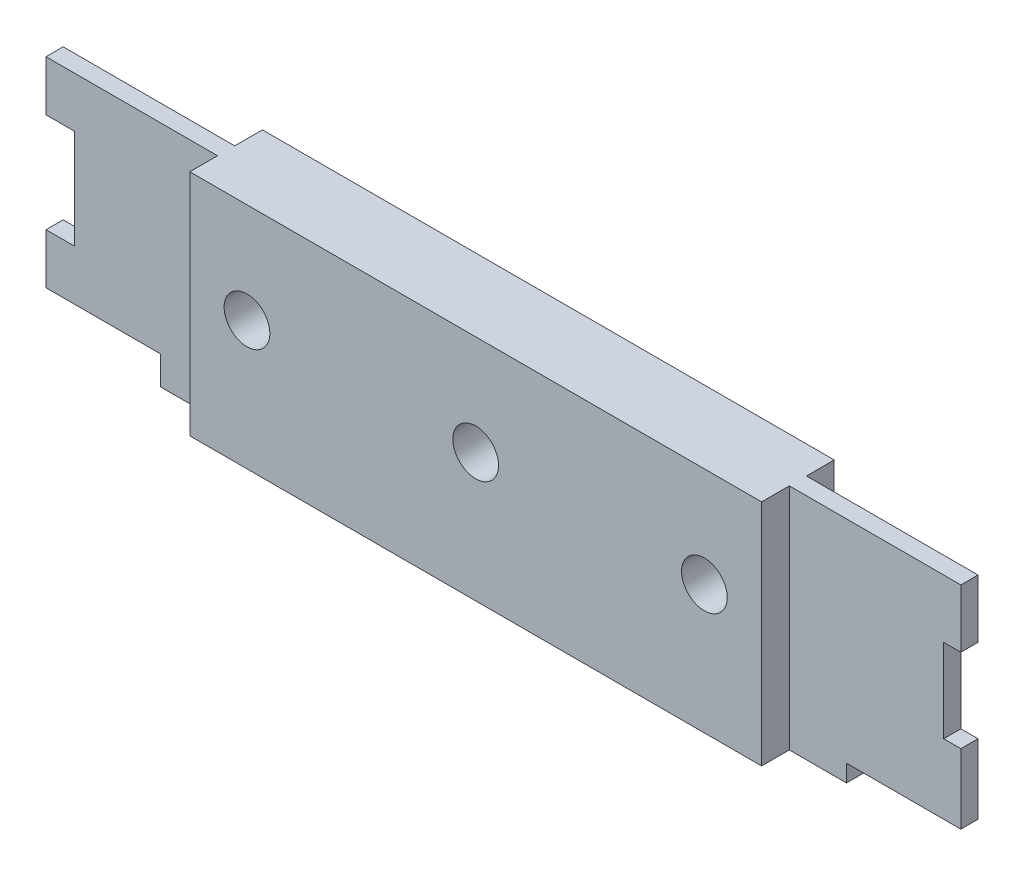
SolidWorks part; units mm, degrees
ref_plane "Alzado" through (0, 0, 0) normal (0, 0, 1) x (1, 0, 0)
ref_plane "Planta" through (0, 0, 0) normal (0, 1, 0) x (1, 0, 0)
ref_plane "Vista lateral" through (0, 0, 0) normal (1, 0, 0) x (0, 0, -1)
sketch "Croquis1" plane through (0, 0, 0) normal (0, 0, 1) x (1, 0, 0)
  line L0 (-40, 8.75) -> (40, 8.75)
  line L1 (40, 8.75) -> (40, 3.65)
  line L2 (40, 3.65) -> (38.5, 3.65)
  line L3 (38.5, 3.65) -> (38.5, -3.65)
  line L4 (38.5, -3.65) -> (40, -3.65)
  line L5 (40, -3.65) -> (40, -9.75)
  line L6 (40, -9.75) -> (30, -9.75)
  line L7 (30, -9.75) -> (30, -11.25)
  line L8 (30, -11.25) -> (-30, -11.25)
  line L9 (-30, -11.25) -> (-30, -8.75)
  line L10 (-30, -8.75) -> (-40, -8.75)
  line L11 (-40, -8.75) -> (-40, -4.35)
  line L12 (-40, -4.35) -> (-37.5, -4.35)
  line L13 (-37.5, -4.35) -> (-37.5, 4.35)
  line L14 (-37.5, 4.35) -> (-40, 4.35)
  line L15 (-40, 4.35) -> (-40, 8.75)
  line L16 (38.5, 0) -> (-37.5, 0) construction
  circle A0 centre (20, 0) radius 2
  circle A1 centre (0, 0) radius 2
  circle A2 centre (-20, 0) radius 2
  point P16 (-37.5, 0)
  point P18 (38.5, 0)
  point P19 (0, 8.75)
  dimension "D9" = 4
  dimension "D10" = 20
  dimension "D11" = 20
  dimension "D12" = 20
  dimension "D1" = 80
  dimension "D2" = 10
  dimension "D3" = 10
  dimension "D4" = 20
  dimension "D5" = 8.7
  dimension "D6" = 7.3
  dimension "D7" = 2.5
  dimension "D8" = 1.5
extrude "Saliente-Extruir1" add sketch "Croquis1" along normal mid plane 1.5
sketch "Croquis2" plane through (0, 0, 0) normal (0, 0, 1) x (1, 0, 0)
  line L0 (40, 8.75) -> (-40, 8.75) construction
  line L1 (-25, 8.75) -> (25, 8.75)
  line L2 (-25, 8.75) -> (-25, -11.25)
  line L3 (-25, -11.25) -> (25, -11.25)
  line L4 (25, 8.75) -> (25, -11.25)
  line L5 (-30, -11.25) -> (30, -11.25) construction
  line L6 (-40, 8.75) -> (-40, 4.35) construction
  line L7 (40, 3.65) -> (40, 8.75) construction
  circle A0 centre (-20, 0) radius 2
  circle A1 centre (0, 0) radius 2
  circle A2 centre (20, 0) radius 2
  dimension "D1" = 15
  dimension "D2" = 15
extrude "Saliente-Extruir2" add sketch "Croquis2" along normal mid plane 6.35
